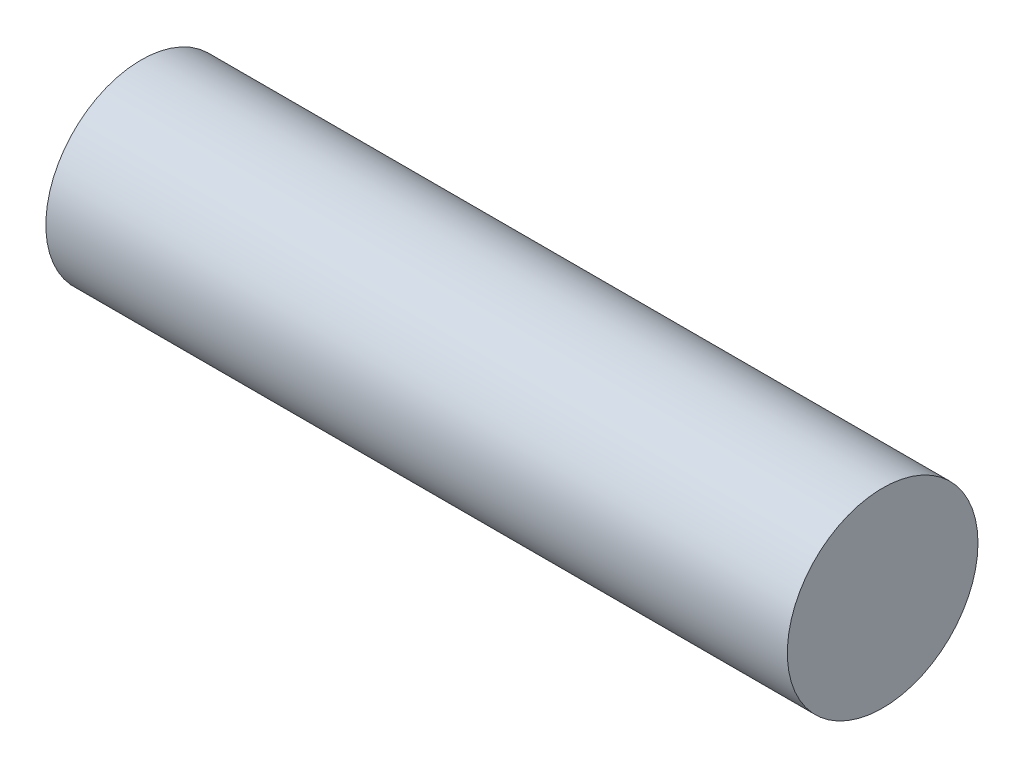
SolidWorks part; units mm, degrees
ref_plane "Front Plane" through (0, 0, 0) normal (0, 0, 1) x (1, 0, 0)
ref_plane "Top Plane" through (0, 0, 0) normal (0, 1, 0) x (1, 0, 0)
ref_plane "Right Plane" through (0, 0, 0) normal (1, 0, 0) x (0, 0, -1)
sketch "Sketch1" plane through (0, 0, 0) normal (1, 0, 0) x (0, 0, -1)
  circle A0 centre (0, 0) radius 9
  dimension "D1" = 18
extrude "Boss-Extrude1" add sketch "Sketch1" along normal blind 70
